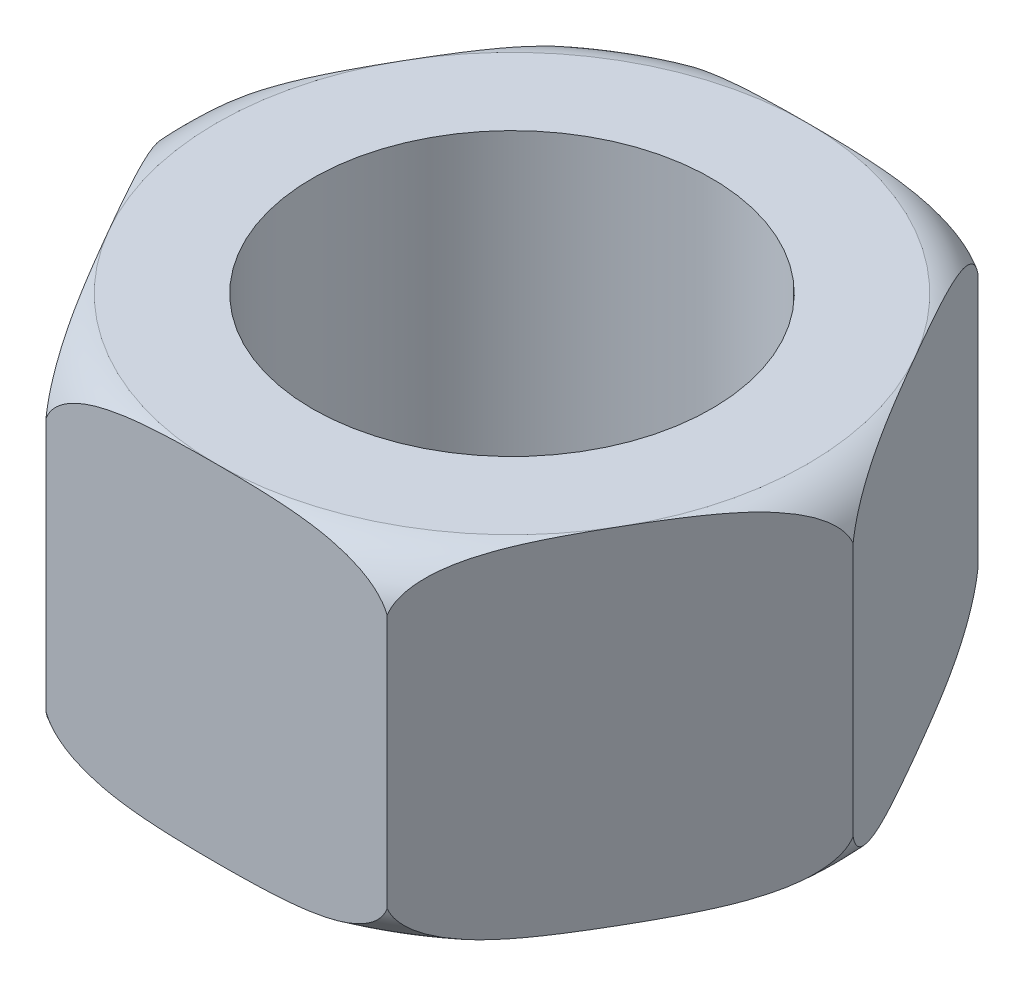
SolidWorks part; units mm, degrees
ref_plane "前视基准面" through (0, 0, 0) normal (0, 0, 1) x (1, 0, 0)
ref_plane "上视基准面" through (0, 0, 0) normal (0, 1, 0) x (1, 0, 0)
ref_plane "右视基准面" through (0, 0, 0) normal (1, 0, 0) x (0, 0, -1)
other "Configuration Table"
sketch "草图1" plane through (0, 0, 0) normal (0, 1, 0) x (1, 0, 0)
  line L0 (0, 0) -> (17.0896, 0) construction
  line L1 (17.0896, 0) -> (8.5448, 14.8)
  line L2 (8.5448, 14.8) -> (-8.5448, 14.8)
  line L3 (-8.5448, 14.8) -> (-17.0896, 0)
  line L4 (-17.0896, 0) -> (-8.5448, -14.8)
  line L5 (-8.5448, -14.8) -> (8.5448, -14.8)
  line L6 (8.5448, -14.8) -> (17.0896, 0)
  circle A0 centre (0, 0) radius 14.8 construction
  circle A1 centre (0, 0) radius 10
  dimension "D1" = 20
  dimension "D2" = 29.6
extrude "凸台-拉伸1" add sketch "草图1" along normal blind 17.3
cosmetic thread "装饰螺纹线1" parameters "D2"=21
sketch "草图2" plane through (0, 0, 0) normal (1, 0, 0) x (0, 0, -1)
  line L0 (0, 0) -> (0, 24.6647) construction
  line L2 (-14.8, 17.3) -> (-14.8, 0) construction
  line L3 (-14.8, 17.3) -> (0, 17.3) construction
  line L4 (-13.8, 17.3) -> (-14.8, 17.3) construction
  line L5 (-14.8, 17.3) -> (-14.8, 16.3) construction
  line L6 (-14.8, 16.3) -> (-15.2661, 16.3)
  line L7 (-15.2661, 16.3) -> (-15.2661, 17.6414)
  line L8 (-15.2661, 17.6414) -> (-13.8, 17.6414)
  line L9 (-13.8, 17.6414) -> (-13.8, 17.3)
  arc A1 (-14.8, 16.3) -> (-13.8, 17.3) centre (-13.2855, 15.7855) cw
  dimension "D1" = 1
  dimension "D2" = 1
ref_plane "基准面1" through (0, 0, 0) normal (0.866, 0, -0.5) x (-0.5, 0, -0.866)
sketch "草图3" plane through (0, 0, 0) normal (0.866, 0, -0.5) x (-0.5, 0, -0.866)
  line L0 (-17.0896, 17.3) -> (-17.0896, 15.0104) construction
  line L1 (-17.0896, 17.3) -> (-17.0896, 0) construction
  line L2 (-17.0896, 17.3) -> (-14.8, 17.3) construction
  line L3 (-17.0896, 17.3) -> (-8.5448, 17.3) construction
  line L4 (0, 0) -> (0, 24.6647) construction
  line L5 (-14.8, 17.3) -> (-14.8, 17.9287)
  line L6 (-14.8, 17.9287) -> (-17.7995, 17.9287)
  line L7 (-17.7995, 17.9287) -> (-17.7995, 15.0104)
  line L8 (-17.7995, 15.0104) -> (-17.0896, 15.0104)
  line L9 (-21.0171, 8.65) -> (21.5783, 8.65) construction
  line L10 (-8.5448, 17.3) -> (8.5448, 17.3) construction
  line L11 (-8.5448, 0) -> (8.5448, 0) construction
  line L12 (-17.0896, 0) -> (-14.8, 0) construction
  line L13 (-17.0896, 0) -> (-17.0896, 2.2896) construction
  line L14 (-17.7995, 2.2896) -> (-17.0896, 2.2896)
  line L15 (-17.7995, -0.6287) -> (-17.7995, 2.2896)
  line L16 (-14.8, -0.6287) -> (-17.7995, -0.6287)
  line L17 (-14.8, 0) -> (-14.8, -0.6287)
  arc A0 (-14.8, 17.3) -> (-17.0896, 15.0104) centre (-14.2837, 14.4942) ccw
  arc A1 (-14.8, 0) -> (-17.0896, 2.2896) centre (-14.2837, 2.8058) cw
  dimension "D2" = 14.8
revolve "切除-旋转4" cut sketch "草图3" angle 360 about L0
